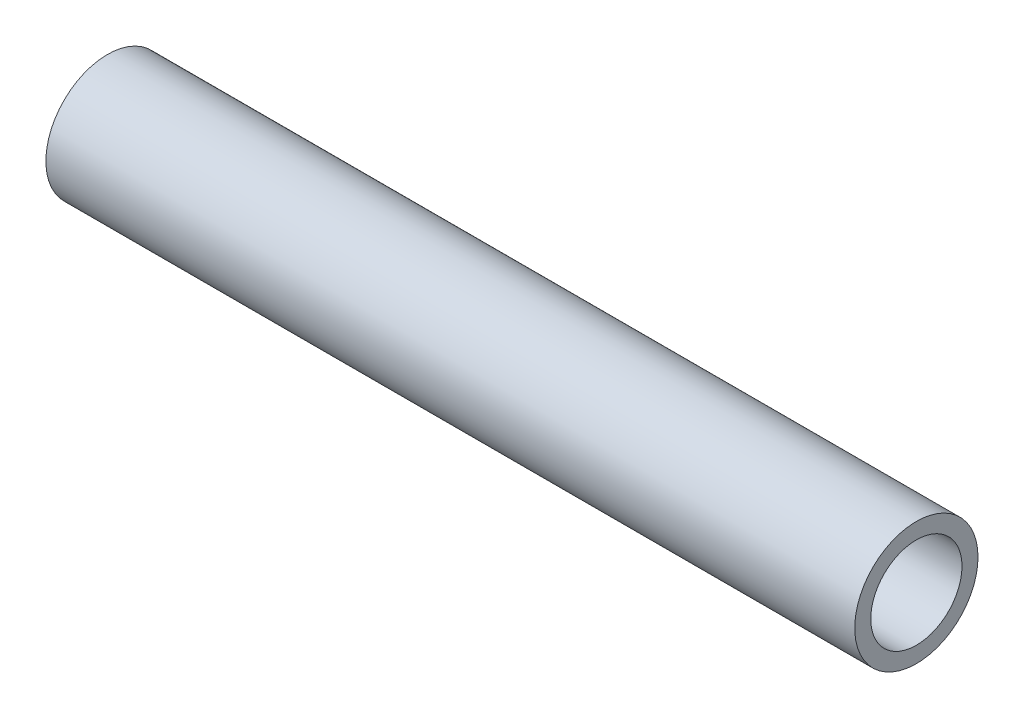
SolidWorks part; units mm, degrees
ref_plane "Front Plane" through (0, 0, 0) normal (0, 0, 1) x (1, 0, 0)
ref_plane "Top Plane" through (0, 0, 0) normal (0, 1, 0) x (1, 0, 0)
ref_plane "Right Plane" through (0, 0, 0) normal (1, 0, 0) x (0, 0, -1)
sketch "Sketch1" plane through (0, 0, 0) normal (0, 1, 0) x (1, 0, 0)
  line L0 (-70, 0) -> (70, 0)
  line L1 (-70, -20.2778) -> (-70, 20.2778)
  line L2 (70, 16.6987) -> (70, -16.6987)
  point P4 (0, 0)
  point P8 (-70, 0)
  point P11 (70, 0)
  dimension "D1" = 140
ref_plane "Plane1" through (-70, 0, 0) normal (1, 0, 0) x (0, 0, -1)
other "Pipe 0.5 SCH 40(1)"
ref_plane "Plane2" through (-70, 0, 0) normal (1, 0, 0) x (0, 0, -1)
sketch "Sketch11" plane through (-70, 0, 0) normal (1, 0, 0) x (0, 0, -1)
  circle A0 centre (0, 0) radius 7.8994
  circle A1 centre (0, 0) radius 10.668
  circle A2 centre (0, 0) radius 6.35 construction
  point P5 (0, 10.668)
  point P6 (0, -10.668)
  point P7 (-10.668, 0)
  point P8 (10.668, 0)
  point P9 (0, 0)
  dimension "In_dia" = 15.7988
  dimension "Out_dia" = 21.336
  dimension "D1" = 12.7
